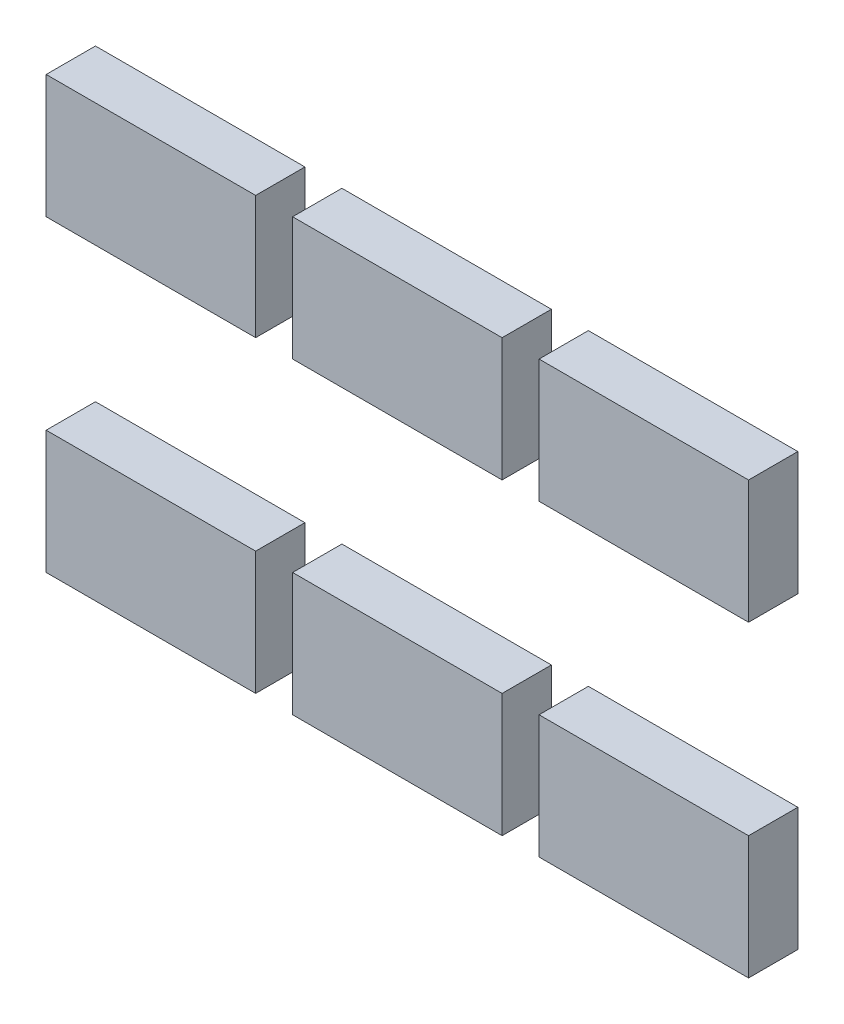
SolidWorks part; units mm, degrees
ref_plane "Спереди" through (0, 0, 0) normal (0, 0, 1) x (1, 0, 0)
ref_plane "Сверху" through (0, 0, 0) normal (0, 1, 0) x (1, 0, 0)
ref_plane "Справа" through (0, 0, 0) normal (1, 0, 0) x (0, 0, -1)
sketch "Эскиз1" plane through (0, 0, 0) normal (0, 0, 1) x (1, 0, 0)
  line L0 (2.3, -1) -> (5.7, -1)
  line L1 (-1.7, -1) -> (1.7, -1)
  line L2 (-1.7, -1) -> (-1.7, 1)
  line L3 (-1.7, 1) -> (1.7, 1)
  line L4 (1.7, -1) -> (1.7, 1)
  line L5 (-1.7, -1) -> (1.7, 1) construction
  line L6 (-1.7, 1) -> (1.7, -1) construction
  line L7 (5.7, -1) -> (5.7, 1)
  line L8 (2.3, 1) -> (5.7, 1)
  line L9 (2.3, -1) -> (2.3, 1)
  line L10 (6.3, -1) -> (9.7, -1)
  line L11 (9.7, -1) -> (9.7, 1)
  line L12 (6.3, 1) -> (9.7, 1)
  line L13 (6.3, -1) -> (6.3, 1)
  line L22 (2.3, 4) -> (5.7, 4)
  line L23 (5.7, 4) -> (5.7, 6)
  line L24 (2.3, 6) -> (5.7, 6)
  line L25 (2.3, 4) -> (2.3, 6)
  line L26 (6.3, 4) -> (9.7, 4)
  line L27 (9.7, 4) -> (9.7, 6)
  line L28 (6.3, 6) -> (9.7, 6)
  line L29 (6.3, 4) -> (6.3, 6)
  line L38 (-1.7, 4) -> (1.7, 4)
  line L39 (1.7, 4) -> (1.7, 6)
  line L40 (-1.7, 6) -> (1.7, 6)
  line L41 (-1.7, 4) -> (-1.7, 6)
  line L42 (10.3, -1) -> (13.7, -1) [skipped]
  line L43 (13.7, -1) -> (13.7, 1) [skipped]
  line L44 (10.3, 1) -> (13.7, 1) [skipped]
  line L45 (10.3, -1) -> (10.3, 1) [skipped]
  line L46 (14.3, -1) -> (17.7, -1) [skipped]
  line L47 (17.7, -1) -> (17.7, 1) [skipped]
  line L48 (14.3, 1) -> (17.7, 1) [skipped]
  line L49 (14.3, -1) -> (14.3, 1) [skipped]
  line L50 (10.3, 4) -> (13.7, 4) [skipped]
  line L51 (13.7, 4) -> (13.7, 6) [skipped]
  line L52 (10.3, 6) -> (13.7, 6) [skipped]
  line L53 (10.3, 4) -> (10.3, 6) [skipped]
  line L54 (14.3, 4) -> (17.7, 4) [skipped]
  line L55 (17.7, 4) -> (17.7, 6) [skipped]
  line L56 (14.3, 6) -> (17.7, 6) [skipped]
  line L57 (14.3, 4) -> (14.3, 6) [skipped]
  point P0 (0, 0)
  dimension "D1" = 3.4
  dimension "D2" = 2
  dimension "D3" = 5
  dimension "D4" = 2
extrude "Бобышка-Вытянуть1" add sketch "Эскиз1" along normal blind 0.8
